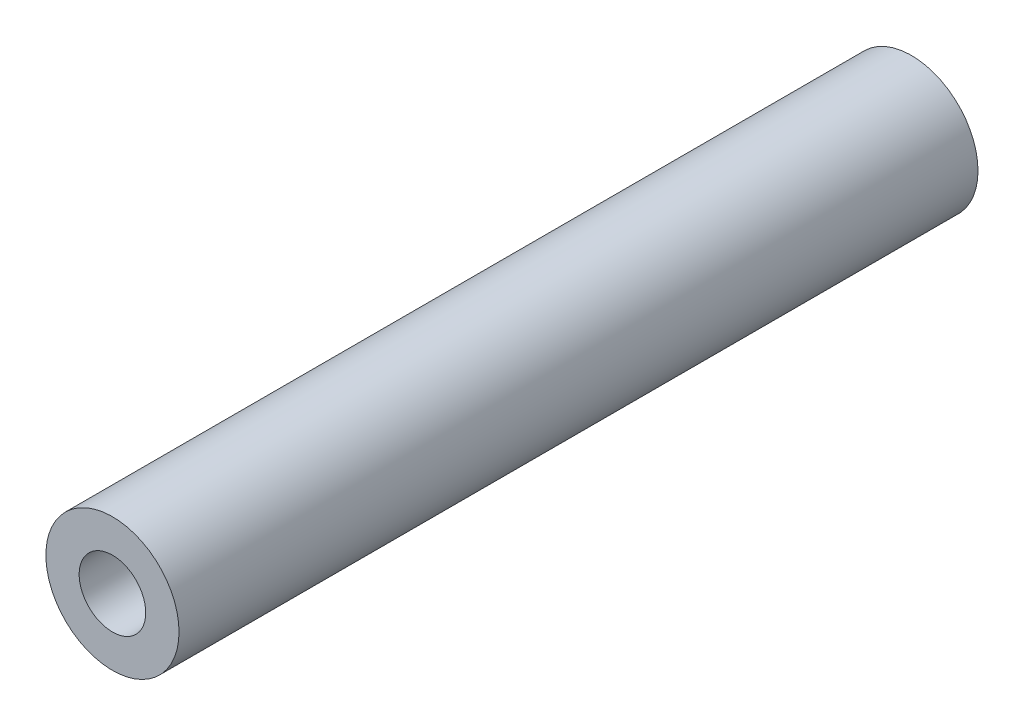
SolidWorks part; units mm, degrees
ref_plane "Front Plane" through (0, 0, 0) normal (1, 0, 0) x (0, 1, 0)
ref_plane "Top Plane" through (0, 0, 0) normal (0, 0, 1) x (0, 1, 0)
ref_plane "Right Plane" through (0, 0, 0) normal (0, 1, 0) x (-1, 0, 0)
sketch "Sketch2" plane through (0, 0, 0) normal (0, 0, 1) x (0, 1, 0)
  circle A0 centre (0, 0) radius 10
  circle A1 centre (0, 0) radius 5
  dimension "D1" = 20
  dimension "D2" = 10
extrude "Boss-Extrude1" add sketch "Sketch2" along normal blind 120
